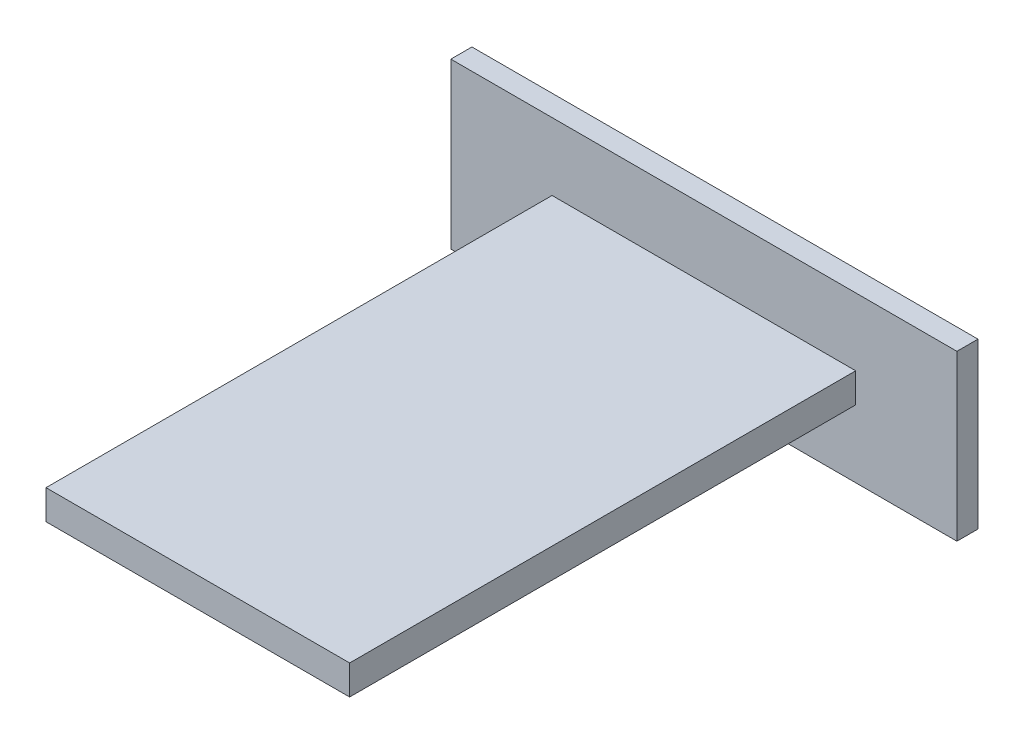
SolidWorks part; units mm, degrees
ref_plane "Front Plane" through (0, 0, 0) normal (0, 0, 1) x (1, 0, 0)
ref_plane "Top Plane" through (0, 0, 0) normal (0, 1, 0) x (1, 0, 0)
ref_plane "Right Plane" through (0, 0, 0) normal (1, 0, 0) x (0, 0, -1)
sketch "Sketch1" plane through (0, 0, 0) normal (0, 1, 0) x (1, 0, 0)
  line L1 (-9, -15) -> (9, -15)
  line L2 (-9, -15) -> (-9, 15)
  line L3 (-9, 15) -> (9, 15)
  line L4 (9, -15) -> (9, 15)
  line L5 (-9, -15) -> (9, 15) construction
  line L6 (-9, 15) -> (9, -15) construction
  point P0 (0, 0)
  dimension "D1" = 18
  dimension "D2" = 30
extrude "Boss-Extrude1" add sketch "Sketch1" along normal blind 1.75
sketch "Sketch2" plane through (0, 0, -15) normal (0, 0, -1) x (-1, 0, 0)
  line L5 (-9, 0.875) -> (9, 0.875) construction
  line L6 (-9, 1.75) -> (-9, 0) construction
  line L7 (9, 1.75) -> (9, 0) construction
  line L9 (-15, -4) -> (15, -4)
  line L10 (-15, -4) -> (-15, 5.75)
  line L11 (-15, 5.75) -> (15, 5.75)
  line L12 (15, -4) -> (15, 5.75)
  line L13 (-15, -4) -> (15, 5.75) construction
  line L14 (-15, 5.75) -> (15, -4) construction
  point P7 (0, 0.875)
  dimension "D1" = 6
  dimension "D2" = 4
extrude "Boss-Extrude2" add sketch "Sketch2" along normal blind 1.25
